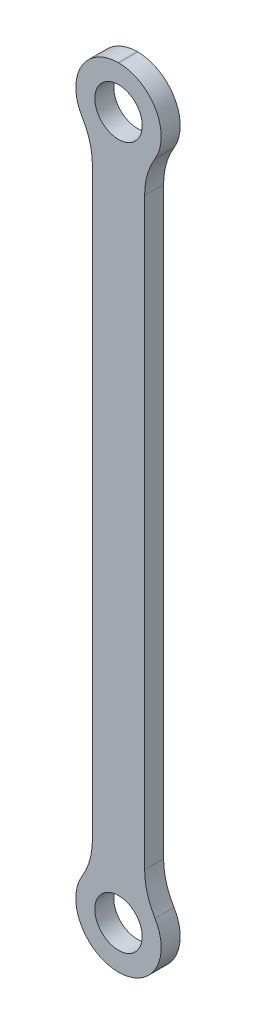
SolidWorks part; units mm, degrees
ref_plane "前视基准面" through (0, 0, 0) normal (0, 0, 1) x (1, 0, 0)
ref_plane "上视基准面" through (0, 0, 0) normal (0, 1, 0) x (1, 0, 0)
ref_plane "右视基准面" through (0, 0, 0) normal (1, 0, 0) x (0, 0, -1)
sketch "草图1" plane through (0, 0, 0) normal (0, 0, 1) x (1, 0, 0)
  line B0 (-5.5, 135.52) -> (-5.5, 12.48)
  line B1 (5.5, 12.48) -> (5.5, 135.52)
  line B2 (-0.1, 156.9994) -> (0.1, 156.9994)
  line B3 (0.1, -8.9994) -> (-0.1, -8.9994)
  arc B4 (5.5, 12.48) -> (7.6875, 4.68) centre (20.5, 12.48) ccw
  arc B5 (-7.6875, 4.68) -> (-0.1, -8.9994) centre (0, 0) ccw
  arc B6 (0.1, -8.9994) -> (7.6875, 4.68) centre (0, 0) ccw
  arc B7 (-7.6875, 4.68) -> (-5.5, 12.48) centre (-20.5, 12.48) ccw
  arc B8 (-5.5, 135.52) -> (-7.6875, 143.32) centre (-20.5, 135.52) ccw
  arc B9 (7.6875, 143.32) -> (0.1, 156.9994) centre (0, 148) ccw
  arc B10 (-0.1, 156.9994) -> (-7.6875, 143.32) centre (0, 148) ccw
  arc B11 (7.6875, 143.32) -> (5.5, 135.52) centre (20.5, 135.52) ccw
  circle B12 centre (0, 0) radius 5
  circle B13 centre (0, 148) radius 5
sketch_block_instance "块1-1"
sketch_block "块1"
extrude "凸台-拉伸1" add sketch "草图1" along normal blind 4
